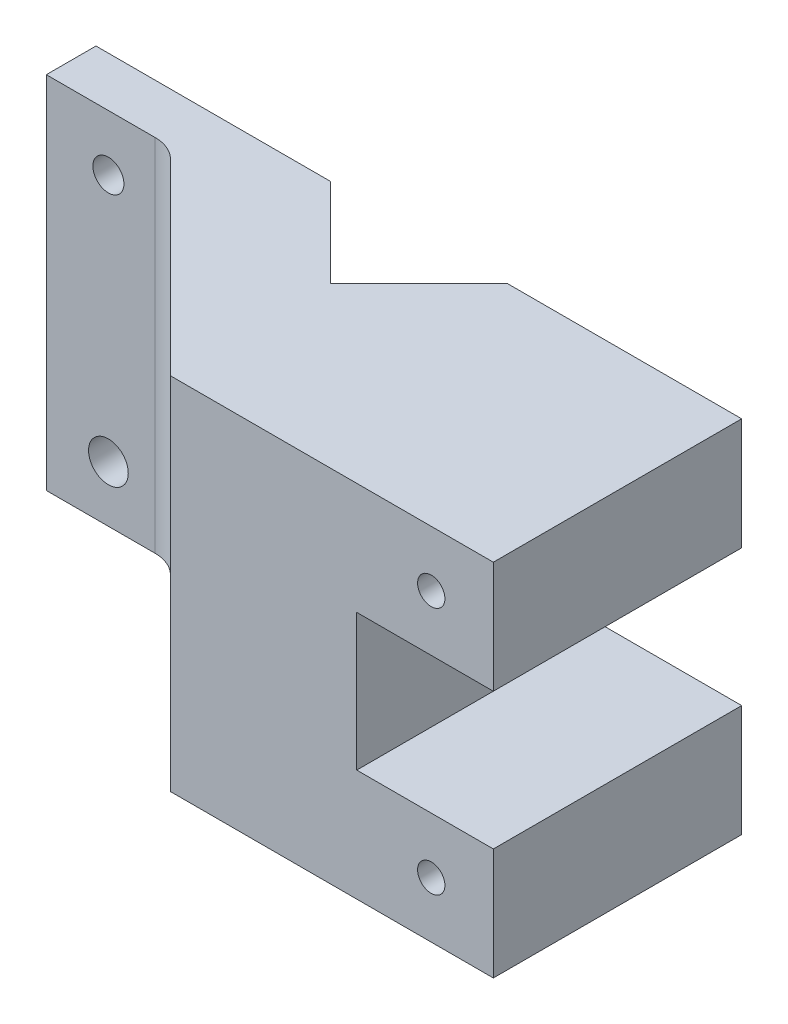
SolidWorks part; units mm, degrees
ref_plane "Front Plane" through (0, 0, 0) normal (0, 0, 1) x (1, 0, 0)
ref_plane "Top Plane" through (0, 0, 0) normal (0, 1, 0) x (1, 0, 0)
ref_plane "Right Plane" through (0, 0, 0) normal (1, 0, 0) x (0, 0, -1)
sketch "Sketch1" plane through (0, 0, 0) normal (0, 1, 0) x (1, 0, 0)
  line L5 (-7.1317, 0) -> (-26, 0)
  line L12 (7.1317, 0) -> (26, 0)
  line L13 (26, 0) -> (26, -20)
  line L14 (26, -20) -> (0, -20)
  line L17 (-26, 0) -> (-26, -4)
  line L19 (-16, -4) -> (0, -20)
  line L20 (-7.1317, 0) -> (0, -7.1317)
  line L21 (0, -7.1317) -> (7.1317, 0)
  line L22 (-26, -4) -> (-16, -4)
  circle A2 centre (0, 1.6718) radius 6.225 construction
  circle A3 centre (0, 1) radius 5.75 construction
  point P0 (0, 0)
  point P1 (0, -20)
  dimension "D5" = 26
  dimension "D9" = 12.45
  dimension "D10" = 11.5
  dimension "D2" = 10
  dimension "D3" = 1
  dimension "D4" = 1.6718
  dimension "D6" = 20
  dimension "D8" = 4
extrude "Boss-Extrude1" add sketch "Sketch1" along normal mid plane 29
sketch "Sketch4" plane through (0, 0, 20) normal (0, 0, 1) x (1, 0, 0)
  line L0 (26, 5.5) -> (15, 5.5)
  line L1 (26, 14.5) -> (26, -14.5) construction
  line L2 (15, 5.5) -> (15, -5.5)
  line L3 (15, -5.5) -> (26, -5.5)
  line L4 (0, 0) -> (26, 0) construction
  line L5 (0, -14.5) -> (26, -14.5) construction
  line L6 (0, 14.5) -> (26, 14.5) construction
  line L7 (26, 5.5) -> (26, -5.5)
  circle A0 centre (21, 10) radius 1.1
  circle A1 centre (21, -10) radius 1.1
  dimension "D1" = 2.2
  dimension "D2" = 2.2
  dimension "D3" = 9
  dimension "D4" = 20
  dimension "D5" = 10
  dimension "D6" = 9
  dimension "D7" = 11
  dimension "D8" = 5
extrude "Cut-Extrude2" cut sketch "Sketch4" against normal through all and the other way through all
sketch "Sketch5" plane through (0, 0, 4) normal (0, 0, 1) x (1, 0, 0)
  line L4 (-26, 0) -> (0, 0) construction
  line L5 (-26, 14.5) -> (-26, -14.5) construction
  circle A0 centre (-21, 10) radius 1.25
  circle A1 centre (-21, -10) radius 1.6
  dimension "D1" = 2.5
  dimension "D2" = 3.2
  dimension "D3" = 5
  dimension "D4" = 20
  dimension "D5" = 10
extrude "Cut-Extrude3" cut sketch "Sketch5" against normal through all
fillet "Fillet1" radius 3 1 edges at (-16, 0, 4)
